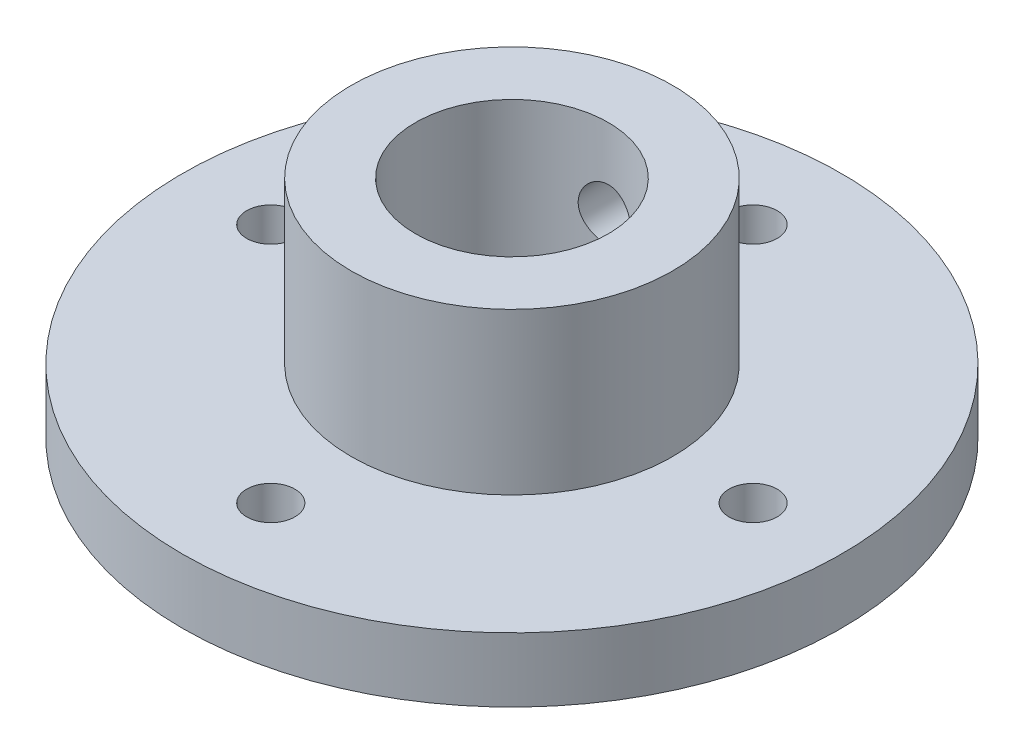
SolidWorks part; units mm, degrees
ref_plane "前视基准面" through (0, 0, 0) normal (0, 0, 1) x (1, 0, 0)
ref_plane "上视基准面" through (0, 0, 0) normal (0, 1, 0) x (1, 0, 0)
ref_plane "右视基准面" through (0, 0, 0) normal (1, 0, 0) x (0, 0, -1)
sketch "Sketch1" plane through (0, 0, 0) normal (1, 0, 0) x (0, 0, -1)
  line L0 (6, 0) -> (6, -14)
  line L1 (6, -14) -> (20.5, -14)
  line L2 (20.5, -14) -> (20.5, -10)
  line L3 (20.5, -10) -> (10, -10)
  line L4 (10, -10) -> (10, 0)
  line L5 (10, 0) -> (6, 0)
  line L6 (0, 12.4625) -> (0, -20.7921) construction
  dimension "D1" = 14
  dimension "D2" = 10
  dimension "D3" = 6
  dimension "D4" = 10
  dimension "D5" = 20.5
revolve "Revolve1" add sketch "Sketch1" angle 360 about L6
sketch "Sketch4" plane through (0, -10, 0) normal (0, 1, 0) x (1, 0, 0)
  circle A0 centre (0, 0) radius 15 construction
  circle A1 centre (0, 15) radius 1.5
  circle A2 centre (15, 0) radius 1.5
  circle A3 centre (0, -15) radius 1.5
  circle A4 centre (-15, 0) radius 1.5
  dimension "D1" = 4
extrude "Cut-Extrude1" cut sketch "Sketch4" against normal up to next
hole_wizard "M4 Tapped Hole1" positions "3DSketch1" profile "Sketch7" tap size "M4" standard "DIN"
sketch3d "3DSketch1"
  line L0 (0, 0, 0) -> (0, -5, 0) construction
  line L1 (0, -5, 0) -> (0, -5, -10) construction
  point P0 (0, -5, -10)
sketch "Sketch7" plane through (0, -5, -10) normal (1, 0, 0) x (0, 1, 0)
  line L0 (0, 0) -> (0, 4)
  line L1 (0, 4) -> (1.65, 4)
  line L2 (1.65, 4) -> (1.65, 0)
  line L5 (1.65, 0) -> (0, 0)
  line L11 (0, -6.35) -> (0, 107.95) construction
  dimension "Thru Tap Drill Dia." = 3.3
  dimension "Thru Tap Drill Depth" = 4
cosmetic thread "Hole Thread1"
